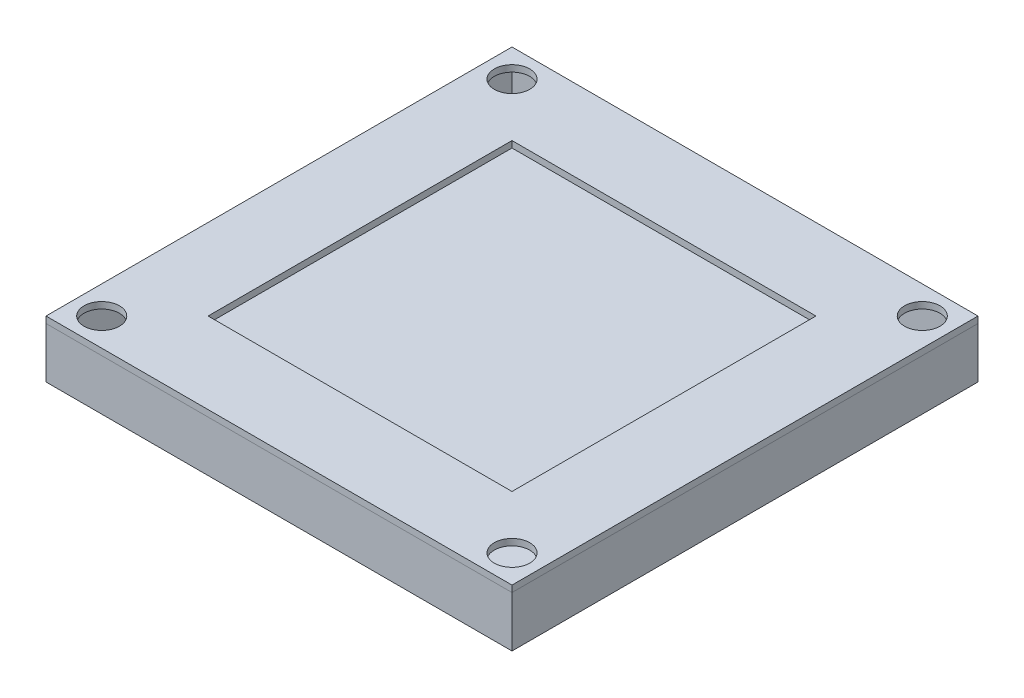
SolidWorks part; units mm, degrees
material "Acrylic (Medium-high impact)"
ref_plane "Front" through (0, 0, 0) normal (0, 0, 1) x (1, 0, 0)
ref_plane "Top" through (0, 0, 0) normal (0, 1, 0) x (1, 0, 0)
ref_plane "Right" through (0, 0, 0) normal (1, 0, 0) x (0, 0, -1)
sketch "Sketch1" plane through (0, 0, 0) normal (0, 1, 0) x (1, 0, 0)
  line L1 (-146.05, 146.05) -> (146.05, 146.05)
  line L2 (-146.05, 146.05) -> (-146.05, -146.05)
  line L3 (-146.05, -146.05) -> (146.05, -146.05)
  line L4 (146.05, 146.05) -> (146.05, -146.05)
  line L5 (-146.05, 146.05) -> (146.05, -146.05) construction
  line L6 (-146.05, -146.05) -> (146.05, 146.05) construction
  line L7 (141.986, 141.986) -> (-141.986, 141.986)
  line L8 (141.986, 141.986) -> (141.986, -141.986)
  line L9 (141.986, -141.986) -> (-141.986, -141.986)
  line L10 (-141.986, 141.986) -> (-141.986, -141.986)
  line L11 (141.986, 141.986) -> (-141.986, -141.986) construction
  line L12 (141.986, -141.986) -> (-141.986, 141.986) construction
  point P0 (0, 0)
  point P6 (0, 0)
  dimension "D1" = 292.1
extrude "Boss-Extrude1" add sketch "Sketch1" along normal blind 31.75
sketch "Sketch2" plane through (0, 0, 0) normal (0, -1, 0) x (1, 0, 0)
  line L4 (146.05, -146.05) -> (146.05, 146.05)
  line L5 (146.05, 146.05) -> (-146.05, 146.05)
  line L6 (-146.05, 146.05) -> (-146.05, -146.05)
  line L7 (-146.05, -146.05) -> (146.05, -146.05)
  line L8 (146.05, -146.05) -> (146.05, 146.05)
  line L9 (146.05, 146.05) -> (-146.05, 146.05)
  line L10 (-146.05, 146.05) -> (-146.05, -146.05)
  line L11 (-146.05, -146.05) -> (146.05, -146.05)
  dimension "D1" = 0
extrude "Boss-Extrude2" add sketch "Sketch2" against normal blind 1.524
sketch "Sketch3" plane through (0, 31.75, 0) normal (0, 1, 0) x (1, 0, 0)
  line L1 (128.5875, -128.5875) -> (-128.5875, -128.5875) construction
  line L2 (128.5875, -128.5875) -> (128.5875, 128.5875) construction
  line L3 (128.5875, 128.5875) -> (-128.5875, 128.5875) construction
  line L4 (146.05, -146.05) -> (146.05, 146.05)
  line L5 (146.05, 146.05) -> (-146.05, 146.05)
  line L6 (-146.05, 146.05) -> (-146.05, -146.05)
  line L7 (-146.05, -146.05) -> (146.05, -146.05)
  line L8 (146.05, -146.05) -> (146.05, 146.05)
  line L9 (146.05, 146.05) -> (-146.05, 146.05)
  line L10 (-146.05, 146.05) -> (-146.05, -146.05)
  line L11 (-146.05, -146.05) -> (146.05, -146.05)
  line L12 (-128.5875, -128.5875) -> (-128.5875, 128.5875) construction
  line L13 (128.5875, -128.5875) -> (-128.5875, 128.5875) construction
  line L14 (128.5875, 128.5875) -> (-128.5875, -128.5875) construction
  line L15 (-95.25, 95.25) -> (95.25, 95.25)
  line L16 (-95.25, 95.25) -> (-95.25, -95.25)
  line L17 (-95.25, -95.25) -> (95.25, -95.25)
  line L18 (95.25, 95.25) -> (95.25, -95.25)
  line L19 (-95.25, 95.25) -> (95.25, -95.25) construction
  line L20 (-95.25, -95.25) -> (95.25, 95.25) construction
  circle A0 centre (-128.5875, 128.5875) radius 11.1125
  circle A1 centre (-128.5875, -128.5875) radius 11.1125
  circle A2 centre (128.5875, -128.5875) radius 11.1125
  circle A3 centre (128.5875, 128.5875) radius 11.1125
  point P2 (0, 0)
  point P14 (0, 0)
  dimension "D2" = 22.225
  dimension "D3" = 257.175
  dimension "D4" = 190.5
  dimension "D1" = 0
extrude "Boss-Extrude3" add sketch "Sketch3" along normal blind 4.064 separate body
equation "\"D1@Boss-Extrude3\"=\"TROUGH MATERIAL THICKNESS\""
